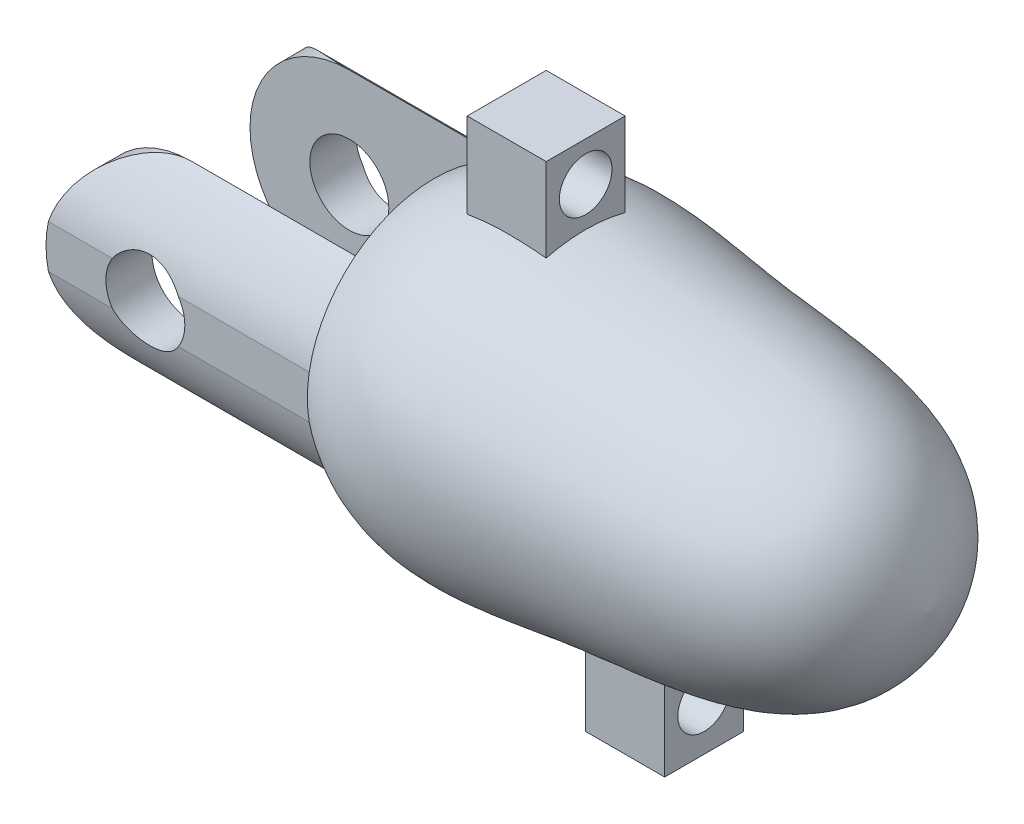
SolidWorks part; units mm, degrees
ref_plane "Front" through (0, 0, 0) normal (0, 0, 1) x (1, 0, 0)
ref_plane "Top" through (0, 0, 0) normal (0, 1, 0) x (1, 0, 0)
ref_plane "Right" through (0, 0, 0) normal (1, 0, 0) x (0, 0, -1)
sketch "Sketch1" plane through (0, 0, 0) normal (0, 0, 1) x (1, 0, 0)
  line L0 (-34.2752, 0) -> (65.3865, 0) construction
  line L1 (-17.5039, 9.6421) -> (-17.5039, 0)
  line L2 (-17.5039, 0) -> (20.1151, 0)
  spline S0 degree 3 poles (-17.5039, 9.6421) (-12.038, 13.468) (1.7207, 9.9869) (18.6749, 10.7604) (20.1151, 0) knots 0 0 0 0 0.417252 1 1 1 1
revolve "Revolve1" add sketch "Sketch1" angle 360 about L0
sketch "Sketch2" plane through (-17.5039, 0, 0) normal (-1, 0, 0) x (0, 0, 1)
  line L1 (-9.5, 10) -> (9.5, 10)
  line L2 (-9.5, 10) -> (-9.5, -10)
  line L3 (-9.5, -10) -> (9.5, -10)
  line L4 (9.5, 10) -> (9.5, -10)
  line L5 (-9.5, 10) -> (9.5, -10) construction
  line L6 (-9.5, -10) -> (9.5, 10) construction
  point P0 (0, 0)
  dimension "D1" = 20
  dimension "D2" = 19
extrude "Boss-Extrude1" add sketch "Sketch2" along normal blind 20
sketch "Sketch3" plane through (-17.5039, 0, 0) normal (-1, 0, 0) x (0, 0, 1)
  circle A0 centre (0, 0) radius 9.6421
  circle A1 centre (0, 0) radius 15
  arc A2 (-9.5, 1.6492) -> (-9.5, -1.6492) centre (0, 0) ccw construction
  dimension "D1" = 30
extrude "Cut-Extrude1" cut sketch "Sketch3" along normal through all
sketch "Sketch4" plane through (0, 0, 0) normal (0, 1, 0) x (1, 0, 0)
  line L0 (-37.5039, 9.5) -> (-37.5039, -9.5) construction
  line L5 (-37.5039, 6) -> (-17.5039, 6)
  line L6 (-37.5039, 6) -> (-37.5039, -6)
  line L7 (-37.5039, -6) -> (-17.5039, -6)
  line L8 (-17.5039, 6) -> (-17.5039, -6)
  line L9 (-17.5039, -9.5) -> (-17.5039, 9.5) construction
  dimension "D1" = 3.5
  dimension "D2" = 3.5
extrude "Cut-Extrude2" cut sketch "Sketch4" against normal through all both and the other way through all
sketch "Sketch6" plane through (0, 0, -6) normal (0, 0, 1) x (1, 0, 0)
  line L0 (-17.5039, -7.5478) -> (-37.5039, -7.5478) construction
  line L1 (-37.5039, 7.5478) -> (-17.5039, 7.5478) construction
  line L2 (-37.5039, -7.5478) -> (-37.5039, 7.5478) construction
  line L3 (-29.9561, -7.5478) -> (-37.5039, -7.5478)
  line L4 (-37.5039, -7.5478) -> (-37.5039, 7.5478)
  line L5 (-37.5039, 7.5478) -> (-29.9561, 7.5478)
  arc A0 (-29.9561, -7.5478) -> (-29.9561, 7.5478) centre (-29.9561, 0) cw
  line M1 (-37.5039, 7.5478) -> (-37.5039, -7.5478)
  line M2 (-37.5039, -7.5478) -> (-17.5039, -7.5478)
  line M4 (-17.5039, 7.5478) -> (-37.5039, 7.5478)
extrude "Cut-Extrude3" cut sketch "Sketch6" against normal through all both and the other way through all contours A0 L4 M2 | A0 M1 M4
sketch "Sketch7" plane through (0, 0, 9.5) normal (0, 0, 1) x (1, 0, 0)
  line L0 (-29.9561, -1.6492) -> (-29.9561, 1.6492) construction
  line L1 (-37.3216, -1.6492) -> (-17.5039, -1.6492) construction
  line L2 (-17.5039, 1.6492) -> (-37.3216, 1.6492) construction
  circle A0 centre (-29.9561, 0) radius 3
  arc A1 (-37.3216, 1.6492) -> (-37.3216, -1.6492) centre (-29.9561, 0) ccw construction
  dimension "D1" = 6
extrude "Cut-Extrude4" cut sketch "Sketch7" against normal through all
sketch "Sketch8" plane through (0, 0, 0) normal (0, 1, 0) x (1, 0, 0)
  line L1 (-3, 3) -> (3, 3)
  line L2 (-3, 3) -> (-3, -3)
  line L3 (-3, -3) -> (3, -3)
  line L4 (3, 3) -> (3, -3)
  line L5 (-3, 3) -> (3, -3) construction
  line L6 (-3, -3) -> (3, 3) construction
  point P0 (0, 0)
  dimension "D1" = 6
  dimension "D2" = 6
extrude "Boss-Extrude3" add sketch "Sketch8" against normal blind 18 contours L4 L3 L2 L1
sketch "Sketch9" plane through (3, 0, 0) normal (1, 0, 0) x (0, 0, -1)
  line L0 (0, -18) -> (0, -11.0047) construction
  line L1 (3, -18) -> (-3, -18) construction
  circle A0 centre (0, -14.5024) radius 2
  arc A1 (-3, -10.5879) -> (3, -10.5879) centre (0, 0) ccw construction
  dimension "D1" = 4
extrude "Cut-Extrude5" cut sketch "Sketch9" against normal blind 16
sketch "Sketch10" plane through (0, 0, 0) normal (0, 1, 0) x (1, 0, 0)
  line L1 (-12, 3) -> (-6, 3)
  line L2 (-12, 3) -> (-12, -3)
  line L3 (-12, -3) -> (-6, -3)
  line L4 (-6, 3) -> (-6, -3)
  line L5 (-12, 3) -> (-6, -3) construction
  line L6 (-12, -3) -> (-6, 3) construction
  point P0 (-9, 0)
  dimension "D1" = 6
  dimension "D2" = 6
  dimension "D3" = 6
extrude "Boss-Extrude4" add sketch "Sketch10" along normal blind 18
sketch "Sketch11" plane through (-6, 0, 0) normal (1, 0, 0) x (0, 0, -1)
  line L0 (0, 18) -> (0, 12.0283) construction
  line L1 (-3, 18) -> (3, 18) construction
  circle A0 centre (0, 15.0142) radius 2
  arc A1 (3, 11.6482) -> (-3, 11.6482) centre (0, 0) ccw construction
  dimension "D1" = 4
extrude "Cut-Extrude6" cut sketch "Sketch11" against normal through all
scale "Scale1" scale about centroid uniform scaling yes scale factor 0.75
